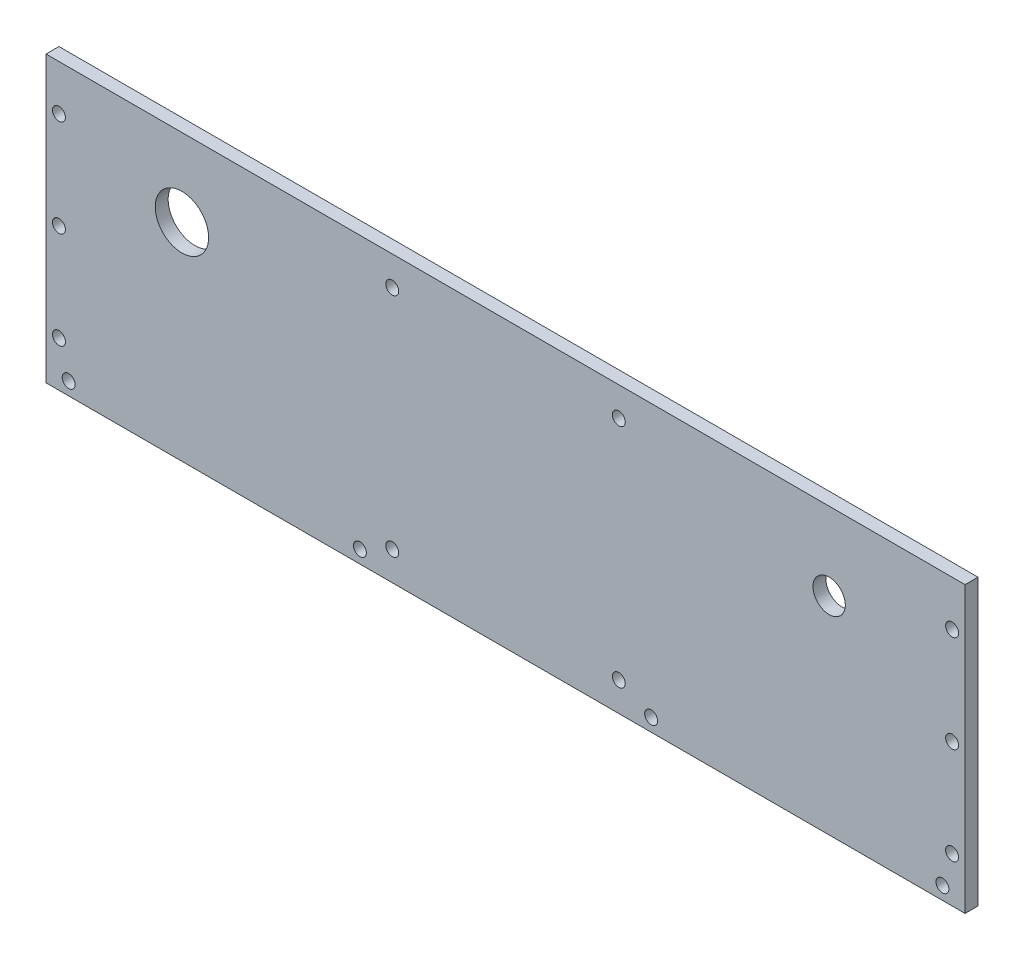
SolidWorks part; units mm, degrees
ref_plane "Front" through (0, 0, 0) normal (0, 0, 1) x (1, 0, 0)
ref_plane "Top" through (0, 0, 0) normal (0, 1, 0) x (1, 0, 0)
ref_plane "Right" through (0, 0, 0) normal (1, 0, 0) x (0, 0, -1)
sketch "Esquisse1" plane through (0, 0, 0) normal (0, 0, 1) x (1, 0, 0)
  line L1 (0, 0) -> (284, 0)
  line L2 (0, 0) -> (0, 88)
  line L3 (0, 88) -> (284, 88)
  line L4 (284, 0) -> (284, 88)
  dimension "D1" = 88
  dimension "D2" = 284
extrude "Boss.-Extru.1" add sketch "Esquisse1" along normal blind 4
sketch "Esquisse2" plane through (0, 0, 4) normal (0, 0, 1) x (1, 0, 0)
  line L0 (142, 0) -> (142, 88) construction
  line L1 (0, 0) -> (284, 0) construction
  line L2 (284, 88) -> (0, 88) construction
  line L3 (142, 44) -> (0, 44) construction
  line L4 (0, 88) -> (0, 0) construction
  line L5 (4, 88) -> (4, 0) construction
  line L6 (280, 88) -> (280, 0) construction
  line L7 (142, 4) -> (0, 4) construction
  line L8 (242, 0) -> (242, 88) construction
  line L9 (242, 64) -> (42, 64) construction
  circle A0 centre (107, 79) radius 2
  circle A1 centre (107, 9) radius 2
  circle A2 centre (177, 9) radius 2
  circle A3 centre (177, 79) radius 2
  circle A4 centre (42, 64) radius 8.25
  circle A5 centre (4, 14) radius 2
  circle A6 centre (4, 74) radius 2
  circle A7 centre (4, 44) radius 2
  circle A8 centre (280, 44) radius 2
  circle A9 centre (280, 74) radius 2
  circle A10 centre (280, 14) radius 2
  circle A11 centre (7, 4) radius 2
  circle A12 centre (97, 4) radius 2
  circle A13 centre (187, 4) radius 2
  circle A14 centre (277, 4) radius 2
  circle A15 centre (242, 64) radius 5
  dimension "D1" = 4
  dimension "D2" = 70
  dimension "D3" = 70
  dimension "D4" = 16.5
  dimension "D8" = 4
  dimension "D10" = 4
  dimension "D12" = 90
  dimension "D13" = 90
  dimension "D14" = 10
  dimension "D5" = 20
  dimension "D6" = 100
  dimension "D7" = 4
  dimension "D9" = 60
  dimension "D11" = 4
  dimension "D15" = 100
extrude "Enlèv. mat.-Extru.1" cut sketch "Esquisse2" against normal through all
